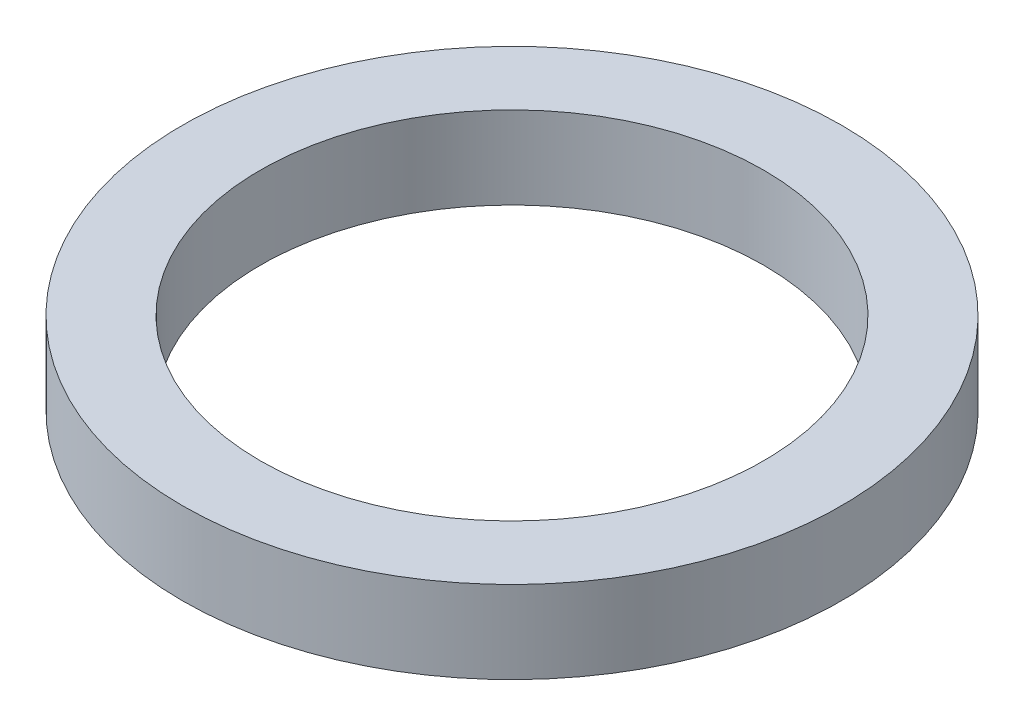
SolidWorks part; units mm, degrees
ref_plane "Front Plane" through (0, 0, 0) normal (0, 0, 1) x (1, 0, 0)
ref_plane "Top Plane" through (0, 0, 0) normal (0, 1, 0) x (1, 0, 0)
ref_plane "Right Plane" through (0, 0, 0) normal (1, 0, 0) x (0, 0, -1)
sketch "Sketch1" plane through (0, 0, 0) normal (0, 1, 0) x (1, 0, 0)
  circle A0 centre (0, 0) radius 27.5
  circle A1 centre (0, 0) radius 36
  dimension "D1" = 55
  dimension "D2" = 72
extrude "Boss-Extrude1" add sketch "Sketch1" along normal mid plane 9
equation "\"Nr\"= 108"
equation "\"module\"= 0.7"
equation "\"pressure_angle\"= 20.0deg"
equation "\"h_a\"= 0.7"
equation "\"h_f\"= 0.875"
equation "\"clr_tip_root\"= 0.17500000000000004"
equation "\"dp_r\"= 75.6"
equation "\"db_r\"= 71.04076213141467"
equation "\"fw_r\"= 8.0"
equation "\"alpha_r\"= 0.8539582918412449"
equation "\"beta_r\"= 3.374583250349157"
equation "\"bearing_ID\"= 55"
equation "\"bearing_OD\"= 72"
equation "\"bearing_height\"= 9"
equation "\"clearance_planet\"= 1.5"
equation "\"case_dist\"= 6.5"
equation "\"Motor_case_OD_max\"= 111.3"
equation "\"case_mounting_PCD\"= 103.8"
equation "\"bearing mount thickness\"= 8"
equation "\"case_mounting_hole_dia\"= 3"
equation "\"output_mounting_PCD\"= 80"
equation "\"output_mounting_hole_dia\"= 4"
equation "\"clearance_case_mount_holes_shell_thickness\"= 1"
equation "\"motor_case_OD_base\"= 101.8"
equation "\"sec_carrier_thickness\"= 5"
equation "\"sun_coupler_hub_thickness\"= 4"
equation "\"clearance_sun_coupler_sec_carrier\"= 1.5"
equation "\"clearance_motor_and_case\"= 5"
equation "\"motor_OD\"= 86.8"
equation "\"Motor_case_thickness\"= 2.5"
equation "\"Motor_case_ID\"= 96.8"
equation "\"case_mounting_hole_shift\"= 1.0"
equation "\"output_mounting_nut_wrench_size\"= 7"
equation "\"output_mounting_nut_thickness\"= 3.2"
equation "\"case_mounting_hole_allen_socket_dia\"= 5.5"
equation "\"output_mounting_nut_depth\"= 3"
equation "\"case_mounting_bolt_depth\"= 4.5"
equation "\"Ns\"= 18"
equation "\"Np\"= 45"
equation "\"ring_radial_thickness\"= 5.0"
equation "\"ring_OD\"= 85.6"
equation "\"ring_to_chamfer_clearance\"= 2"
equation "\"Motor_case_OD_base_to_chamfer\"= 5"
equation "\"pattern_offset_from_motor_case_OD_base\"= 3"
equation "\"pattern_bulge_dia\"= 3"
equation "\"pattern_num_bulge\"= 18"
equation "\"pattern_depth\"= 2"
equation "\"motor_height\"= 26.5"
equation "\"case_mounting_wrench_size\"= 5.5"
equation "\"case_mounting_nut_clearance\"= 2"
equation "\"base_plate_thickness\"= 4"
equation "\"case_mounting_nut_thickness\"= 2.4"
equation "\"case_mounting_surface_height\"= 4"
equation "\"motor_mount_hole_PCD\"= 32"
equation "\"motor_mount_hole_dia\"= 4"
equation "\"motor_mount_hole_num\"= 4"
equation "\"central_hole_offset_from_motor_mount_PCD\"= 5"
equation "\"wire_slot_dist_from_center\"= 30"
equation "\"wire_slot_length\"= 10"
equation "\"wire_slot_radius\"= 4"
equation "\"driver_upper_holes_dist_from_center\"= 23"
equation "\"driver_lower_holes_dist_from_center\"= 15"
equation "\"driver_side_holes_dist_from_center\"= 20"
equation "\"driver_mount_holes_dia\"= 2.5"
equation "\"driver_mount_inserts_OD\"= 3.5"
equation "\"driver_mount_thickness\"= 1.5"
equation "\"driver_mount_height\"= 4"
equation "\"air_flow_hole_offset\"= 3"
equation "\"num_planet\"= 3"
equation "\"planet_pin_bolt_dia\"= 5"
equation "\"planet_pin_socket_head_dia\"= 8.5"
equation "\"carrier_PCD\"= 44.099999999999994"
equation "\"planet_shaft_dia\"= 8"
equation "\"fw_p\"= 8.0"
equation "\"planet_shaft_step_offset\"= 1"
equation "\"carrier_trapezoidal_support_sun_offset\"= 5"
equation "\"carrier_trapezoidal_support_hole_PCD_offset_bearing_ID\"= 4"
equation "\"carrier_trapezoidal_support_hole_dia\"= 3"
equation "\"carrier_trapezoidal_support_hole_socket_head_dia\"= 5.5"
equation "\"carrier_bearing_step_width\"= 1.5"
equation "\"standard_clearance_1_5mm\"= 1.5"
equation "\"standard_fillet_1_5mm\"= 1.5"
equation "\"sun_shaft_bearing_OD\"= 16"
equation "\"sun_shaft_bearing_width\"= 5"
equation "\"standard_bearing_insertion_chamfer\"= 0.5"
equation "\"D1@Sketch1\"=\"bearing_ID\""
equation "\"D2@Sketch1\"=\"bearing_OD\""
equation "\"D1@Boss-Extrude1\"=\"bearing_height\""
equation "\"D7@Sketch2\"=\"carrier_trapezoidal_support_hole_dia\""
equation "\"D5@Sketch2\"= 360 / ( 4 * \"Ns\" ) - \"alpha_s\""
equation "\"D3@Sketch2\"=\"dp_s\"- 2*\"h_b\""
equation "\"D9@Sketch2\"=\"carrier_trapezoidal_support_sun_offset\""
equation "\"carrier_trapezoidal_support_hole_wrench_size\"= 5.5"
equation "\"planet_pin_bolt_wrench_size\"= 8"
equation "\"pressure angle\"= 20.0deg"
equation "\"motor_output_hole_PCD\"= 23"
equation "\"motor_output_hole_dia\"= 4"
equation "\"motor_output_hole_num\"= 4"
equation "\"h_b\"= 0.875"
equation "\"dp_s\"= 12.6"
equation "\"db_s\"= 11.840127021902445"
equation "\"fw_s_calc\"= 6.9645987548691926"
equation "\"alpha_s\"= 0.8539582918412556"
equation "\"beta_s\"= 8.292083416317489"
equation "\"dp_p\"= 31.499999999999996"
equation "\"db_p\"= 29.600317554756113"
equation "\"alpha_p\"= 0.8539582918412343"
equation "\"beta_p\"= 2.2920834163175314"
equation "\"planet_bearing_OD\"= 12"
equation "\"planet_bearing_width\"= 3.5"
equation "\"planet_bore\"= 10"
equation "\"sun_shaft_bearing_ID\"= 8"
equation "\"sun_hub_dia\"= 33.0"
equation "\"sun_central_bolt_dia\"= 5"
equation "\"sun_central_bolt_socket_head_dia\"= 8.5"
equation "\"fw_s_used\"= 16.0"
equation "\"motor_output_hole_CSK_OD\"= 8"
equation "\"motor_output_hole_CSK_head_height\"= 2.0"
equation "\"bearing_retainer_thickness\"= 2"
